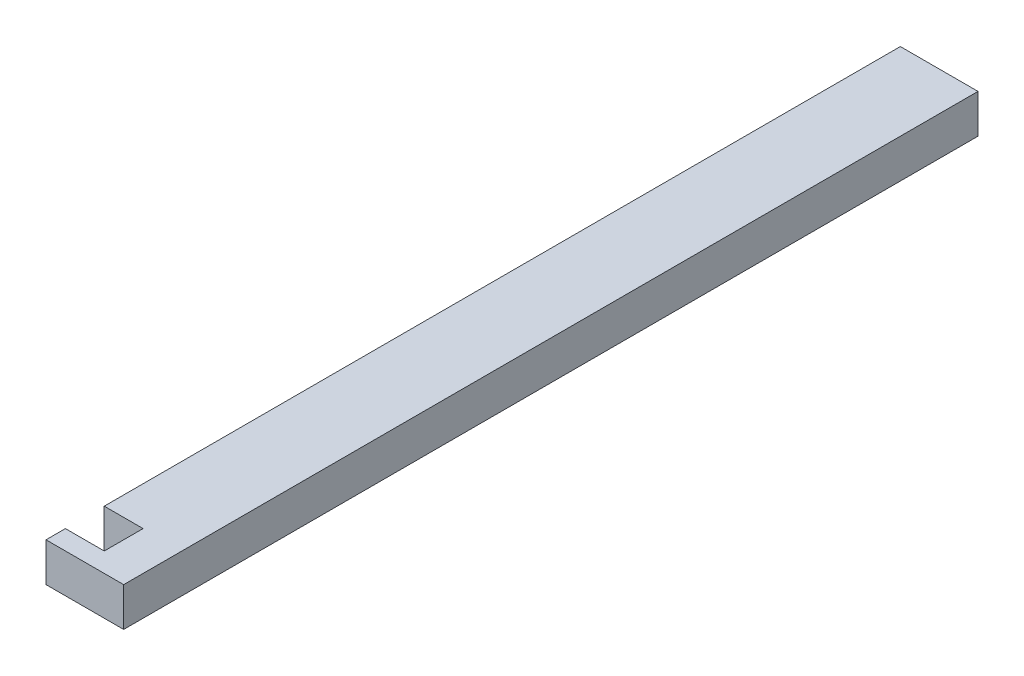
SolidWorks part; units mm, degrees
ref_plane "Front Plane" through (0, 0, 0) normal (0, 0, 1) x (1, 0, 0)
ref_plane "Top Plane" through (0, 0, 0) normal (0, 1, 0) x (1, 0, 0)
ref_plane "Right Plane" through (0, 0, 0) normal (1, 0, 0) x (0, 0, -1)
sketch "Sketch1" plane through (0, 0, 0) normal (0, 0, 1) x (1, 0, 0)
  line L1 (-50.8, -25.4) -> (50.8, -25.4)
  line L2 (-50.8, -25.4) -> (-50.8, 25.4)
  line L3 (-50.8, 25.4) -> (50.8, 25.4)
  line L4 (50.8, -25.4) -> (50.8, 25.4)
  line L5 (-50.8, -25.4) -> (50.8, 25.4) construction
  line L6 (-50.8, 25.4) -> (50.8, -25.4) construction
  point P0 (0, 0)
  dimension "D1" = 50.8
  dimension "D2" = 101.6
extrude "Boss-Extrude1" add sketch "Sketch1" along normal blind 1219.2
sketch "Sketch2" plane through (0, 0, 1219.2) normal (0, 0, 1) x (1, 0, 0)
  line L4 (50.8, -25.4) -> (50.8, 25.4)
  line L5 (50.8, 25.4) -> (-50.8, 25.4)
  line L6 (-50.8, 25.4) -> (-50.8, -25.4)
  line L7 (-50.8, -25.4) -> (50.8, -25.4)
  line L8 (50.8, -25.4) -> (50.8, 25.4)
  line L9 (50.8, 25.4) -> (-50.8, 25.4)
  line L10 (-50.8, 25.4) -> (-50.8, -25.4)
  line L11 (-50.8, -25.4) -> (50.8, -25.4)
  dimension "D1" = 0
extrude "Cut-Extrude1" cut sketch "Sketch2" against normal blind 101.6
sketch "Sketch3" plane through (-50.8, 0, 0) normal (-1, 0, 0) x (0, 0, 1)
  line L0 (1117.6, 25.4) -> (1092.2, 25.4) construction
  line L1 (1117.6, 25.4) -> (0, 25.4) construction
  line L2 (1117.6, -25.4) -> (0, -25.4) construction
  line L3 (1092.2, 25.4) -> (1041.4, 25.4)
  line L4 (1092.2, 25.4) -> (1092.2, -25.4)
  line L5 (1092.2, -25.4) -> (1041.4, -25.4)
  line L6 (1041.4, 25.4) -> (1041.4, -25.4)
  dimension "D1" = 25.4
  dimension "D2" = 50.8
extrude "Cut-Extrude2" cut sketch "Sketch3" against normal blind 50.8
